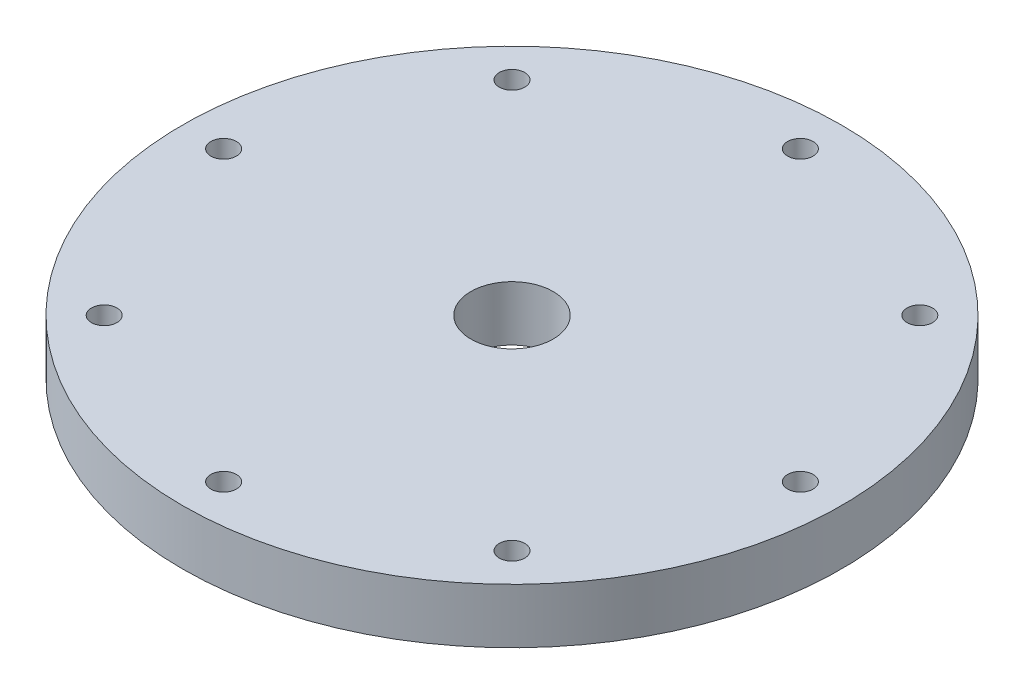
SolidWorks part; units mm, degrees
ref_plane "Front Plane" through (0, 0, 0) normal (0, 0, 1) x (1, 0, 0)
ref_plane "Top Plane" through (0, 0, 0) normal (0, 1, 0) x (1, 0, 0)
ref_plane "Right Plane" through (0, 0, 0) normal (1, 0, 0) x (0, 0, -1)
sketch "Sketch1" plane through (0, 0, 0) normal (0, 1, 0) x (1, 0, 0)
  circle A0 centre (0, 0) radius 38.1
  dimension "D1" = 76.2
extrude "Boss-Extrude1" add sketch "Sketch1" along normal blind 6.35
sketch "Sketch2" plane through (0, 0, 0) normal (0, -1, 0) x (1, 0, 0)
  circle A0 centre (0, 0) radius 33.3375
  circle A1 centre (0, 33.3375) radius 0.762
  dimension "D1" = 66.675
hole_wizard "CBORE for #4 Button Head Cap Screw1" positions "Sketch5" profile "Sketch4" counterbore size "#4" standard "ANSI Inch" end condition through all
sketch "Sketch5" plane through (0, 0, 0) normal (0, -1, 0) x (-1, 0, 0)
  point P0 (0, -33.3375)
sketch "Sketch4" plane through (0, 0, 33.3375) normal (1, 0, 0) x (0, 0, -1)
  line L0 (0, 0) -> (0, 6.35)
  line L1 (0, 6.35) -> (1.4732, 6.35)
  line L3 (1.4732, 6.35) -> (1.4732, 1.4986)
  line L4 (1.4732, 1.4986) -> (2.8575, 1.4986)
  line L5 (2.8575, 1.4986) -> (2.8575, 0)
  line L7 (2.8575, 0) -> (0, 0)
  line L11 (0, -6.35) -> (0, 107.95) construction
  dimension "Thru Hole Dia." = 2.9464
  dimension "Thru Hole Depth" = 6.35
  dimension "C'Bore Dia." = 5.715
  dimension "C'Bore Depth" = 1.4986
pattern_circular "CirPattern1" count 8 over 360 about axis through (0, 0, 0) along (0, 1, 0) of "CBORE for #4 Button Head Cap Screw1"
sketch "Sketch6" plane through (0, 6.35, 0) normal (0, 1, 0) x (1, 0, 0)
  circle A0 centre (0, 0) radius 28.575
  dimension "D1" = 57.15
sketch "Sketch8" plane through (0, 0, 0) normal (0, -1, 0) x (1, 0, 0)
  circle A0 centre (0, 0) radius 4.7625
  dimension "D1" = 9.525
extrude "Cut-Extrude1" cut sketch "Sketch8" against normal through all
